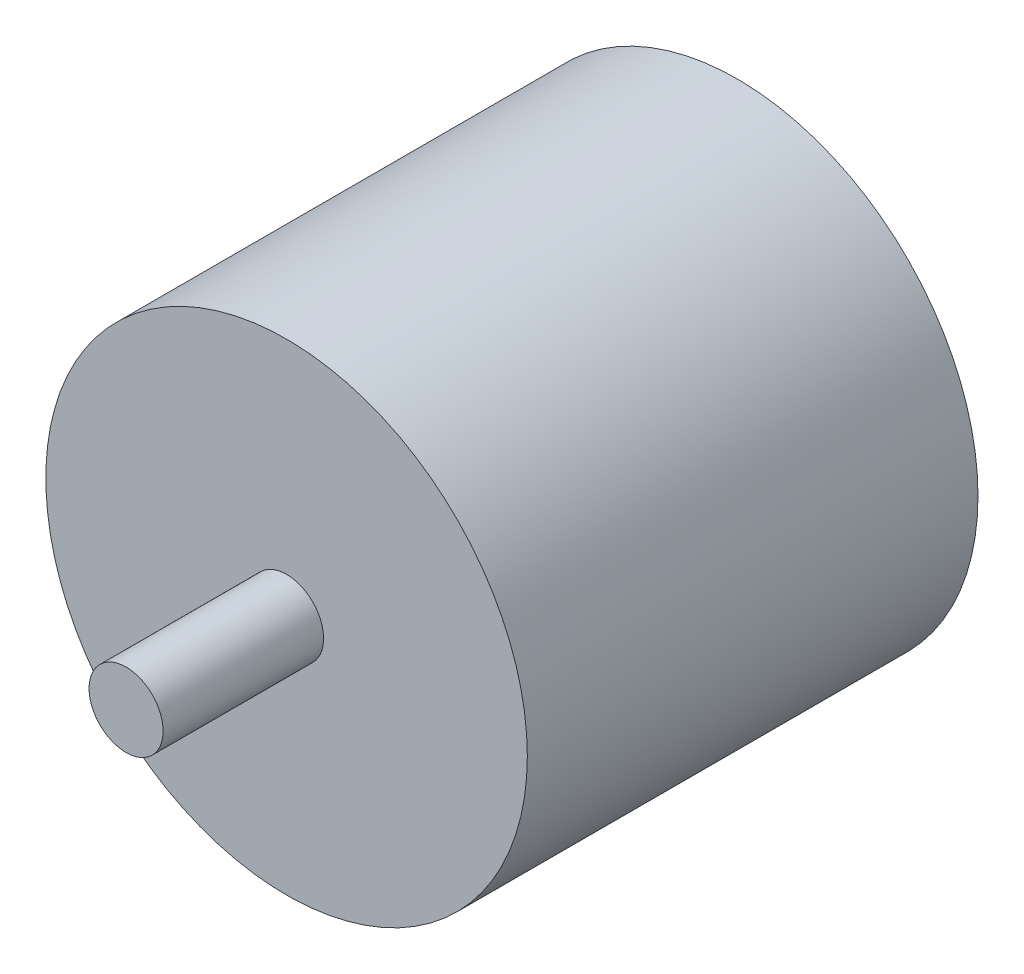
SolidWorks part; units mm, degrees
ref_plane "Front Plane" through (0, 0, 0) normal (0, 0, 1) x (1, 0, 0)
ref_plane "Top Plane" through (0, 0, 0) normal (0, 1, 0) x (1, 0, 0)
ref_plane "Right Plane" through (0, 0, 0) normal (1, 0, 0) x (0, 0, -1)
sketch "Sketch1" plane through (0, 0, 0) normal (0, 0, 1) x (1, 0, 0)
  circle A0 centre (0, 0) radius 19.5
extrude "Boss-Extrude1" add sketch "Sketch1" against normal blind 36.5
sketch "Sketch2" plane through (0, 0, 0) normal (0, 0, 1) x (1, 0, 0)
  circle A0 centre (0, 0) radius 3
extrude "Boss-Extrude2" add sketch "Sketch2" along normal blind 13
